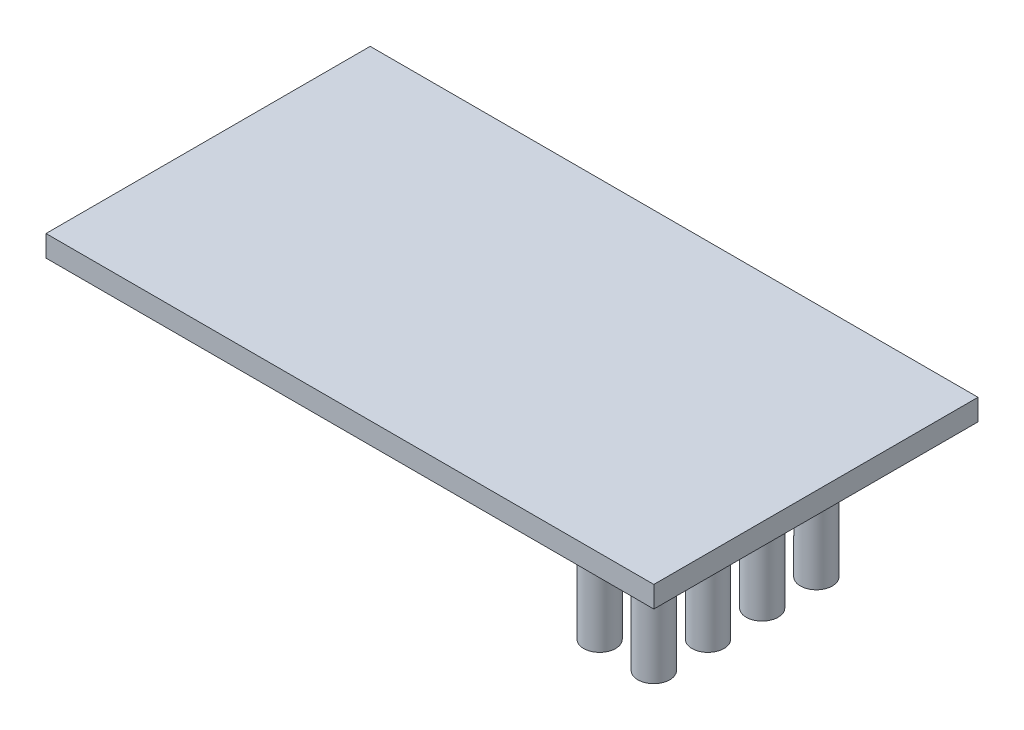
SolidWorks part; units mm, degrees
ref_plane "Front Plane" through (0, 0, 0) normal (0, 0, 1) x (1, 0, 0)
ref_plane "Top Plane" through (0, 0, 0) normal (0, 1, 0) x (1, 0, 0)
ref_plane "Right Plane" through (0, 0, 0) normal (1, 0, 0) x (0, 0, -1)
sketch "Sketch1" plane through (0, 0, 0) normal (0, 1, 0) x (1, 0, 0)
  line L0 (0, 0) -> (0, 15.2)
  line L1 (0, 15.2) -> (28.5, 15.2)
  line L2 (28.5, 15.2) -> (28.5, 0)
  line L3 (28.5, 0) -> (0, 0)
  dimension "D1" = 15.2
  dimension "D2" = 28.5
extrude "Boss-Extrude1" add sketch "Sketch1" along normal blind 1
sketch "Sketch5" plane through (0, 1, 0) normal (0, 1, 0) x (1, 0, 0)
  line L0 (28.5, 0) -> (27, 0)
  line L1 (0, 0) -> (28.5, 0) construction
  line L2 (27, 0) -> (27, 1.5)
  line L3 (27, 1.5) -> (24.46, 1.5)
  circle A0 centre (27, 1.5) radius 0.75
  circle A1 centre (24.46, 1.5) radius 0.75
  circle A2 centre (24.46, 4.04) radius 0.75
  circle A3 centre (27, 4.04) radius 0.75
  circle A4 centre (24.46, 6.58) radius 0.75
  circle A5 centre (27, 6.58) radius 0.75
  circle A6 centre (24.46, 9.12) radius 0.75
  circle A7 centre (27, 9.12) radius 0.75
  dimension "D2" = 1.5
  dimension "D4" = 1.5
  dimension "D1" = 1.5
  dimension "D3" = 1.5
  dimension "D5" = 2.54
  dimension "D7" = 2.54
  dimension "D6" = 4
extrude "Boss-Extrude4" add sketch "Sketch5" against normal blind 5 contours A6 | A7 | A5 | A4 | A2 | A3 | A1 | A0
